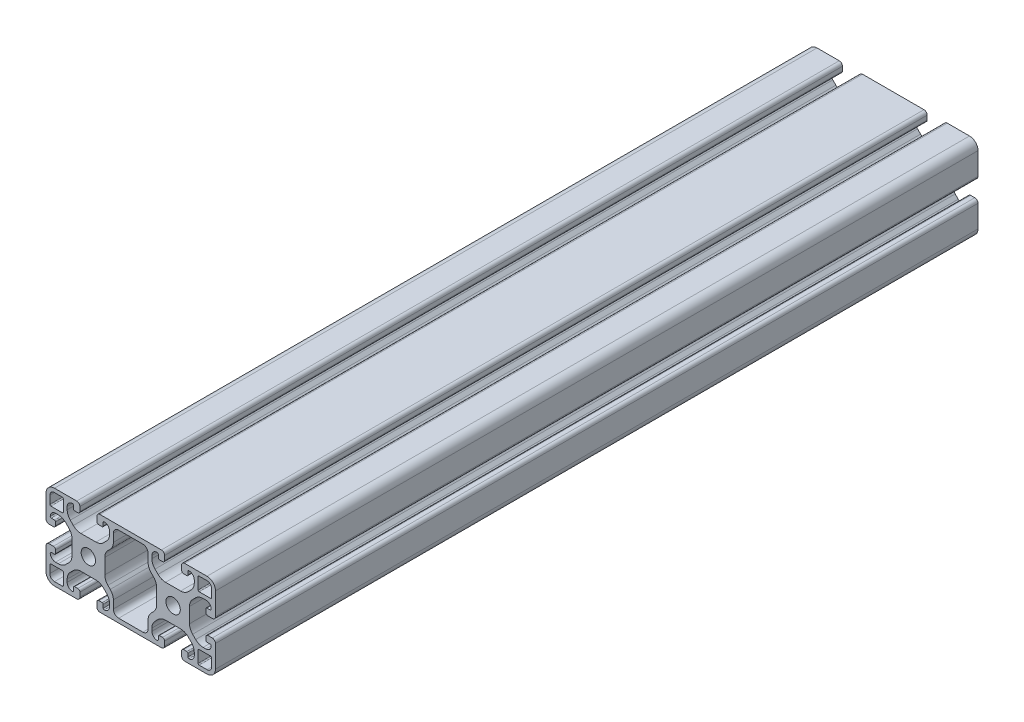
SolidWorks part; units mm, degrees
ref_plane "Plan de face" through (0, 0, 0) normal (0, 0, 1) x (1, 0, 0)
ref_plane "Plan de dessus" through (0, 0, 0) normal (0, 1, 0) x (1, 0, 0)
ref_plane "Plan de droite" through (0, 0, 0) normal (1, 0, 0) x (0, 0, -1)
ref_plane "Plan1" through (0, 0, 20) normal (0, 0, 1) x (1, 0, 0)
sketch "Esquisse1" plane through (0, 0, 20) normal (0, 0, 1) x (1, 0, 0)
  line L0 (66.5, 4.5) -> (65, 4.5)
  line L1 (64, 3.5) -> (64, 1.5)
  line L2 (65.5, 0) -> (76, 0)
  line L3 (80, 4) -> (80, 14.5)
  line L4 (78.5, 16) -> (76.5, 16)
  line L5 (75.5, 15) -> (75.5, 13.5)
  line L6 (76, 13) -> (77.5, 13)
  line L7 (75.5, 10) -> (74.1924, 10)
  line L8 (70.6569, 11.4645) -> (69.2145, 12.9069)
  line L9 (67.75, 16.4424) -> (67.75, 23.5576)
  line L10 (69.2145, 27.0931) -> (70.6569, 28.5355)
  line L11 (74.1924, 30) -> (75.5, 30)
  line L12 (77.5, 27) -> (76, 27)
  line L13 (75.5, 26.5) -> (75.5, 25)
  line L14 (76.5, 24) -> (78.5, 24)
  line L15 (80, 25.5) -> (80, 36)
  line L16 (76, 40) -> (65.5, 40)
  line L17 (64, 38.5) -> (64, 36.5)
  line L18 (65, 35.5) -> (66.5, 35.5)
  line L19 (67, 36) -> (67, 37.5)
  line L20 (70, 35.5) -> (70, 34.1924)
  line L21 (68.5355, 30.6569) -> (67.0931, 29.2145)
  line L22 (63.5576, 27.75) -> (56.4424, 27.75)
  line L23 (52.9069, 29.2145) -> (51.4645, 30.6569)
  line L24 (50, 34.1924) -> (50, 35.5)
  line L25 (53, 37.5) -> (53, 36)
  line L26 (53.5, 35.5) -> (55, 35.5)
  line L27 (56, 36.5) -> (56, 38.5)
  line L28 (54.5, 40) -> (25.5, 40)
  line L29 (24, 38.5) -> (24, 36.5)
  line L30 (25, 35.5) -> (26.5, 35.5)
  line L31 (27, 36) -> (27, 37.5)
  line L32 (30, 35.5) -> (30, 34.1924)
  line L33 (28.5355, 30.6569) -> (27.0931, 29.2145)
  line L34 (23.5576, 27.75) -> (16.4424, 27.75)
  line L35 (12.9069, 29.2145) -> (11.4645, 30.6569)
  line L36 (10, 34.1924) -> (10, 35.5)
  line L37 (13, 37.5) -> (13, 36)
  line L38 (13.5, 35.5) -> (15, 35.5)
  line L39 (16, 36.5) -> (16, 38.5)
  line L40 (14.5, 40) -> (4, 40)
  line L41 (0, 36) -> (0, 25.5)
  line L42 (1.5, 24) -> (3.5, 24)
  line L43 (4.5, 25) -> (4.5, 26.5)
  line L44 (4, 27) -> (2.5, 27)
  line L45 (4.5, 30) -> (5.8076, 30)
  line L46 (9.3431, 28.5355) -> (10.7855, 27.0931)
  line L47 (12.25, 23.5576) -> (12.25, 16.4424)
  line L48 (10.7855, 12.9069) -> (9.3431, 11.4645)
  line L49 (5.8076, 10) -> (4.5, 10)
  line L50 (2.5, 13) -> (4, 13)
  line L51 (4.5, 13.5) -> (4.5, 15)
  line L52 (3.5, 16) -> (1.5, 16)
  line L53 (0, 14.5) -> (0, 4)
  line L54 (4, 0) -> (14.5, 0)
  line L55 (16, 1.5) -> (16, 3.5)
  line L56 (15, 4.5) -> (13.5, 4.5)
  line L57 (13, 4) -> (13, 2.5)
  line L58 (10, 4.5) -> (10, 5.8076)
  line L59 (11.4645, 9.3431) -> (12.9069, 10.7855)
  line L60 (16.4424, 12.25) -> (23.5576, 12.25)
  line L61 (27.0931, 10.7855) -> (28.5355, 9.3431)
  line L62 (30, 5.8076) -> (30, 4.5)
  line L63 (27, 2.5) -> (27, 4)
  line L64 (26.5, 4.5) -> (25, 4.5)
  line L65 (24, 3.5) -> (24, 1.5)
  line L66 (25.5, 0) -> (54.5, 0)
  line L67 (56, 1.5) -> (56, 3.5)
  line L68 (55, 4.5) -> (53.5, 4.5)
  line L69 (53, 4) -> (53, 2.5)
  line L70 (50, 4.5) -> (50, 5.8076)
  line L71 (51.4645, 9.3431) -> (52.9069, 10.7855)
  line L72 (56.4424, 12.25) -> (63.5576, 12.25)
  line L73 (67.0931, 10.7855) -> (68.5355, 9.3431)
  line L74 (70, 5.8076) -> (70, 4.5)
  line L75 (67, 2.5) -> (67, 4)
  line L76 (31.8, 4.5) -> (31.8, 8.2503)
  line L77 (30.3355, 11.7858) -> (29.2145, 12.9069)
  line L78 (27.75, 16.4424) -> (27.75, 23.5576)
  line L79 (29.2145, 27.0931) -> (30.3355, 28.2142)
  line L80 (31.8, 31.7497) -> (31.8, 35.5)
  line L81 (34.3, 38) -> (45.7, 38)
  line L82 (48.2, 35.5) -> (48.2, 31.7497)
  line L83 (49.6645, 28.2142) -> (50.7855, 27.0931)
  line L84 (52.25, 23.5576) -> (52.25, 16.4424)
  line L85 (50.7855, 12.9069) -> (49.6645, 11.7858)
  line L86 (48.2, 8.2503) -> (48.2, 4.5)
  line L87 (45.7, 2) -> (34.3, 2)
  line L88 (7.7, 1.8) -> (4, 1.8)
  line L89 (1.8, 4) -> (1.8, 7.7)
  line L90 (2.3, 8.2) -> (7.7, 8.2)
  line L91 (8.2, 7.7) -> (8.2, 2.3)
  line L92 (72.3, 38.2) -> (76, 38.2)
  line L93 (78.2, 36) -> (78.2, 32.3)
  line L94 (77.7, 31.8) -> (72.3, 31.8)
  line L95 (71.8, 32.3) -> (71.8, 37.7)
  line L96 (78.2, 7.7) -> (78.2, 4)
  line L97 (76, 1.8) -> (72.3, 1.8)
  line L98 (71.8, 2.3) -> (71.8, 7.7)
  line L99 (72.3, 8.2) -> (77.7, 8.2)
  line L100 (1.8, 32.3) -> (1.8, 36)
  line L101 (4, 38.2) -> (7.7, 38.2)
  line L102 (8.2, 37.7) -> (8.2, 32.3)
  line L103 (7.7, 31.8) -> (2.3, 31.8)
  arc A0 (67, 4) -> (66.5, 4.5) centre (66.5, 4) ccw
  arc A1 (65, 4.5) -> (64, 3.5) centre (65, 3.5) ccw
  arc A2 (64, 1.5) -> (65.5, 0) centre (65.5, 1.5) ccw
  arc A3 (76, 0) -> (80, 4) centre (76, 4) ccw
  arc A4 (80, 14.5) -> (78.5, 16) centre (78.5, 14.5) ccw
  arc A5 (76.5, 16) -> (75.5, 15) centre (76.5, 15) ccw
  arc A6 (75.5, 13.5) -> (76, 13) centre (76, 13.5) ccw
  arc A7 (77.5, 13) -> (78, 12.5) centre (77.5, 12.5) cw
  arc A8 (78, 12.5) -> (75.5, 10) centre (75.5, 12.5) cw
  arc A9 (74.1924, 10) -> (70.6569, 11.4645) centre (74.1924, 15) cw
  arc A10 (69.2145, 12.9069) -> (67.75, 16.4424) centre (72.75, 16.4424) cw
  arc A11 (67.75, 23.5576) -> (69.2145, 27.0931) centre (72.75, 23.5576) cw
  arc A12 (70.6569, 28.5355) -> (74.1924, 30) centre (74.1924, 25) cw
  arc A13 (75.5, 30) -> (78, 27.5) centre (75.5, 27.5) cw
  arc A14 (78, 27.5) -> (77.5, 27) centre (77.5, 27.5) cw
  arc A15 (76, 27) -> (75.5, 26.5) centre (76, 26.5) ccw
  arc A16 (75.5, 25) -> (76.5, 24) centre (76.5, 25) ccw
  arc A17 (78.5, 24) -> (80, 25.5) centre (78.5, 25.5) ccw
  arc A18 (80, 36) -> (76, 40) centre (76, 36) ccw
  arc A19 (65.5, 40) -> (64, 38.5) centre (65.5, 38.5) ccw
  arc A20 (64, 36.5) -> (65, 35.5) centre (65, 36.5) ccw
  arc A21 (66.5, 35.5) -> (67, 36) centre (66.5, 36) ccw
  arc A22 (67, 37.5) -> (67.5, 38) centre (67.5, 37.5) cw
  arc A23 (67.5, 38) -> (70, 35.5) centre (67.5, 35.5) cw
  arc A24 (70, 34.1924) -> (68.5355, 30.6569) centre (65, 34.1924) cw
  arc A25 (67.0931, 29.2145) -> (63.5576, 27.75) centre (63.5576, 32.75) cw
  arc A26 (56.4424, 27.75) -> (52.9069, 29.2145) centre (56.4424, 32.75) cw
  arc A27 (51.4645, 30.6569) -> (50, 34.1924) centre (55, 34.1924) cw
  arc A28 (50, 35.5) -> (52.5, 38) centre (52.5, 35.5) cw
  arc A29 (52.5, 38) -> (53, 37.5) centre (52.5, 37.5) cw
  arc A30 (53, 36) -> (53.5, 35.5) centre (53.5, 36) ccw
  arc A31 (55, 35.5) -> (56, 36.5) centre (55, 36.5) ccw
  arc A32 (56, 38.5) -> (54.5, 40) centre (54.5, 38.5) ccw
  arc A33 (25.5, 40) -> (24, 38.5) centre (25.5, 38.5) ccw
  arc A34 (24, 36.5) -> (25, 35.5) centre (25, 36.5) ccw
  arc A35 (26.5, 35.5) -> (27, 36) centre (26.5, 36) ccw
  arc A36 (27, 37.5) -> (27.5, 38) centre (27.5, 37.5) cw
  arc A37 (27.5, 38) -> (30, 35.5) centre (27.5, 35.5) cw
  arc A38 (30, 34.1924) -> (28.5355, 30.6569) centre (25, 34.1924) cw
  arc A39 (27.0931, 29.2145) -> (23.5576, 27.75) centre (23.5576, 32.75) cw
  arc A40 (16.4424, 27.75) -> (12.9069, 29.2145) centre (16.4424, 32.75) cw
  arc A41 (11.4645, 30.6569) -> (10, 34.1924) centre (15, 34.1924) cw
  arc A42 (10, 35.5) -> (12.5, 38) centre (12.5, 35.5) cw
  arc A43 (12.5, 38) -> (13, 37.5) centre (12.5, 37.5) cw
  arc A44 (13, 36) -> (13.5, 35.5) centre (13.5, 36) ccw
  arc A45 (15, 35.5) -> (16, 36.5) centre (15, 36.5) ccw
  arc A46 (16, 38.5) -> (14.5, 40) centre (14.5, 38.5) ccw
  arc A47 (4, 40) -> (0, 36) centre (4, 36) ccw
  arc A48 (0, 25.5) -> (1.5, 24) centre (1.5, 25.5) ccw
  arc A49 (3.5, 24) -> (4.5, 25) centre (3.5, 25) ccw
  arc A50 (4.5, 26.5) -> (4, 27) centre (4, 26.5) ccw
  arc A51 (2.5, 27) -> (2, 27.5) centre (2.5, 27.5) cw
  arc A52 (2, 27.5) -> (4.5, 30) centre (4.5, 27.5) cw
  arc A53 (5.8076, 30) -> (9.3431, 28.5355) centre (5.8076, 25) cw
  arc A54 (10.7855, 27.0931) -> (12.25, 23.5576) centre (7.25, 23.5576) cw
  arc A55 (12.25, 16.4424) -> (10.7855, 12.9069) centre (7.25, 16.4424) cw
  arc A56 (9.3431, 11.4645) -> (5.8076, 10) centre (5.8076, 15) cw
  arc A57 (4.5, 10) -> (2, 12.5) centre (4.5, 12.5) cw
  arc A58 (2, 12.5) -> (2.5, 13) centre (2.5, 12.5) cw
  arc A59 (4, 13) -> (4.5, 13.5) centre (4, 13.5) ccw
  arc A60 (4.5, 15) -> (3.5, 16) centre (3.5, 15) ccw
  arc A61 (1.5, 16) -> (0, 14.5) centre (1.5, 14.5) ccw
  arc A62 (0, 4) -> (4, 0) centre (4, 4) ccw
  arc A63 (14.5, 0) -> (16, 1.5) centre (14.5, 1.5) ccw
  arc A64 (16, 3.5) -> (15, 4.5) centre (15, 3.5) ccw
  arc A65 (13.5, 4.5) -> (13, 4) centre (13.5, 4) ccw
  arc A66 (13, 2.5) -> (12.5, 2) centre (12.5, 2.5) cw
  arc A67 (12.5, 2) -> (10, 4.5) centre (12.5, 4.5) cw
  arc A68 (10, 5.8076) -> (11.4645, 9.3431) centre (15, 5.8076) cw
  arc A69 (12.9069, 10.7855) -> (16.4424, 12.25) centre (16.4424, 7.25) cw
  arc A70 (23.5576, 12.25) -> (27.0931, 10.7855) centre (23.5576, 7.25) cw
  arc A71 (28.5355, 9.3431) -> (30, 5.8076) centre (25, 5.8076) cw
  arc A72 (30, 4.5) -> (27.5, 2) centre (27.5, 4.5) cw
  arc A73 (27.5, 2) -> (27, 2.5) centre (27.5, 2.5) cw
  arc A74 (27, 4) -> (26.5, 4.5) centre (26.5, 4) ccw
  arc A75 (25, 4.5) -> (24, 3.5) centre (25, 3.5) ccw
  arc A76 (24, 1.5) -> (25.5, 0) centre (25.5, 1.5) ccw
  arc A77 (54.5, 0) -> (56, 1.5) centre (54.5, 1.5) ccw
  arc A78 (56, 3.5) -> (55, 4.5) centre (55, 3.5) ccw
  arc A79 (53.5, 4.5) -> (53, 4) centre (53.5, 4) ccw
  arc A80 (53, 2.5) -> (52.5, 2) centre (52.5, 2.5) cw
  arc A81 (52.5, 2) -> (50, 4.5) centre (52.5, 4.5) cw
  arc A82 (50, 5.8076) -> (51.4645, 9.3431) centre (55, 5.8076) cw
  arc A83 (52.9069, 10.7855) -> (56.4424, 12.25) centre (56.4424, 7.25) cw
  arc A84 (63.5576, 12.25) -> (67.0931, 10.7855) centre (63.5576, 7.25) cw
  arc A85 (68.5355, 9.3431) -> (70, 5.8076) centre (65, 5.8076) cw
  arc A86 (70, 4.5) -> (67.5, 2) centre (67.5, 4.5) cw
  arc A87 (67.5, 2) -> (67, 2.5) centre (67.5, 2.5) cw
  circle A88 centre (20, 20) radius 3.4
  circle A89 centre (60, 20) radius 3.4
  arc A90 (34.3, 2) -> (31.8, 4.5) centre (34.3, 4.5) cw
  arc A91 (31.8, 8.2503) -> (30.3355, 11.7858) centre (26.8, 8.2503) ccw
  arc A92 (29.2145, 12.9069) -> (27.75, 16.4424) centre (32.75, 16.4424) cw
  arc A93 (27.75, 23.5576) -> (29.2145, 27.0931) centre (32.75, 23.5576) cw
  arc A94 (30.3355, 28.2142) -> (31.8, 31.7497) centre (26.8, 31.7497) ccw
  arc A95 (31.8, 35.5) -> (34.3, 38) centre (34.3, 35.5) cw
  arc A96 (45.7, 38) -> (48.2, 35.5) centre (45.7, 35.5) cw
  arc A97 (48.2, 31.7497) -> (49.6645, 28.2142) centre (53.2, 31.7497) ccw
  arc A98 (50.7855, 27.0931) -> (52.25, 23.5576) centre (47.25, 23.5576) cw
  arc A99 (52.25, 16.4424) -> (50.7855, 12.9069) centre (47.25, 16.4424) cw
  arc A100 (49.6645, 11.7858) -> (48.2, 8.2503) centre (53.2, 8.2503) ccw
  arc A101 (48.2, 4.5) -> (45.7, 2) centre (45.7, 4.5) cw
  arc A102 (8.2, 2.3) -> (7.7, 1.8) centre (7.7, 2.3) cw
  arc A103 (4, 1.8) -> (1.8, 4) centre (4, 4) cw
  arc A104 (1.8, 7.7) -> (2.3, 8.2) centre (2.3, 7.7) cw
  arc A105 (7.7, 8.2) -> (8.2, 7.7) centre (7.7, 7.7) cw
  arc A106 (71.8, 37.7) -> (72.3, 38.2) centre (72.3, 37.7) cw
  arc A107 (76, 38.2) -> (78.2, 36) centre (76, 36) cw
  arc A108 (78.2, 32.3) -> (77.7, 31.8) centre (77.7, 32.3) cw
  arc A109 (72.3, 31.8) -> (71.8, 32.3) centre (72.3, 32.3) cw
  arc A110 (77.7, 8.2) -> (78.2, 7.7) centre (77.7, 7.7) cw
  arc A111 (78.2, 4) -> (76, 1.8) centre (76, 4) cw
  arc A112 (72.3, 1.8) -> (71.8, 2.3) centre (72.3, 2.3) cw
  arc A113 (71.8, 7.7) -> (72.3, 8.2) centre (72.3, 7.7) cw
  arc A114 (2.3, 31.8) -> (1.8, 32.3) centre (2.3, 32.3) cw
  arc A115 (1.8, 36) -> (4, 38.2) centre (4, 36) cw
  arc A116 (7.7, 38.2) -> (8.2, 37.7) centre (7.7, 37.7) cw
  arc A117 (8.2, 32.3) -> (7.7, 31.8) centre (7.7, 32.3) cw
extrude "Boss.-Extru.1" add sketch "Esquisse1" against normal blind 360
